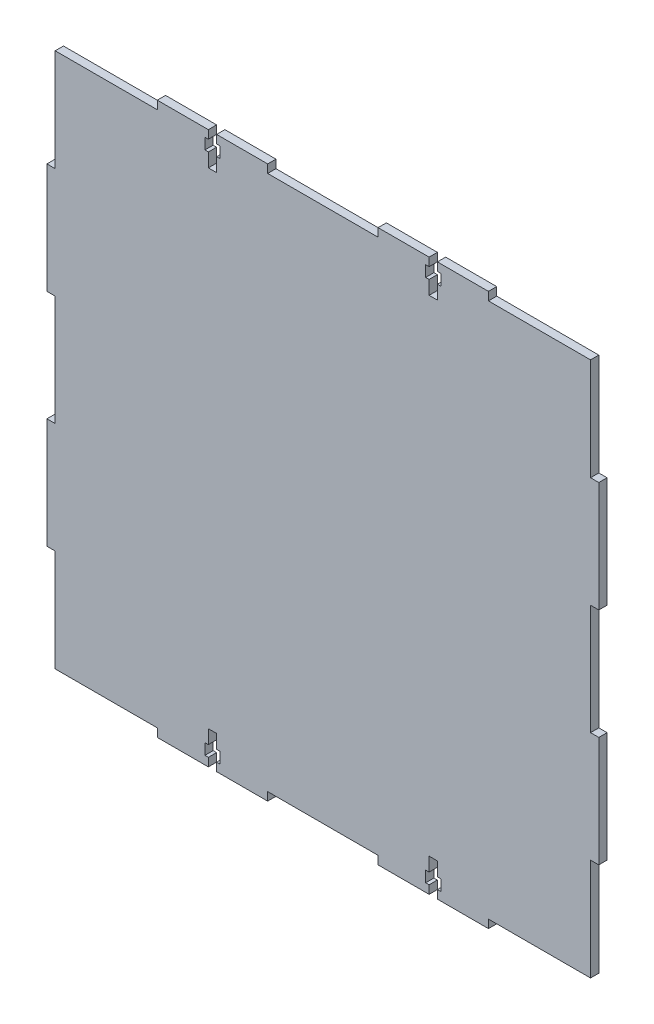
SolidWorks part; units mm, degrees
ref_plane "前视基准面" through (0, 0, 0) normal (0, 0, 1) x (1, 0, 0)
ref_plane "上视基准面" through (0, 0, 0) normal (0, 1, 0) x (1, 0, 0)
ref_plane "右视基准面" through (0, 0, 0) normal (1, 0, 0) x (0, 0, -1)
sketch "草图1" plane through (0, 0, 0) normal (0, 0, 1) x (1, 0, 0)
  line L0 (100, 0) -> (100, -200)
  line L1 (0, 0) -> (200, 0)
  line L2 (0, 0) -> (0, -200)
  line L3 (0, -200) -> (200, -200)
  line L4 (200, 0) -> (200, -200)
  line L5 (0, 0) -> (40, 0)
  line L6 (0, 0) -> (0, -3)
  line L7 (0, -3) -> (40, -3)
  line L8 (40, 0) -> (40, -3)
  line L9 (0, -100) -> (200, -100)
  line L10 (80, 0) -> (80, -3)
  line L11 (80, 0) -> (120, 0)
  line L12 (120, 0) -> (120, -3)
  line L13 (80, -3) -> (120, -3)
  line L14 (160, 0) -> (160, -3)
  line L15 (160, 0) -> (200, 0)
  line L16 (200, 0) -> (200, -3)
  line L17 (160, -3) -> (200, -3)
  line L18 (0, 0) -> (80, 0) construction
  line L19 (200, 0) -> (197, 0)
  line L20 (200, 0) -> (200, -40)
  line L21 (200, -40) -> (197, -40)
  line L22 (197, 0) -> (197, -40)
  line L23 (200, -80) -> (197, -80)
  line L24 (197, -80) -> (197, -120)
  line L25 (200, -120) -> (197, -120)
  line L26 (200, -80) -> (200, -120)
  line L27 (200, -160) -> (197, -160)
  line L28 (197, -160) -> (197, -200)
  line L29 (200, -200) -> (197, -200)
  line L30 (200, -160) -> (200, -200)
  line L31 (200, -200) -> (200, -197)
  line L32 (200, -200) -> (160, -200)
  line L33 (160, -200) -> (160, -197)
  line L34 (200, -197) -> (160, -197)
  line L35 (120, -200) -> (120, -197)
  line L36 (120, -197) -> (80, -197)
  line L37 (80, -200) -> (80, -197)
  line L38 (120, -200) -> (80, -200)
  line L39 (40, -200) -> (40, -197)
  line L40 (40, -197) -> (0, -197)
  line L41 (0, -200) -> (0, -197)
  line L42 (40, -200) -> (0, -200)
  line L43 (0, -200) -> (3, -200)
  line L44 (0, -200) -> (0, -160)
  line L45 (0, -160) -> (3, -160)
  line L46 (3, -200) -> (3, -160)
  line L47 (0, -120) -> (3, -120)
  line L48 (3, -120) -> (3, -80)
  line L49 (0, -80) -> (3, -80)
  line L50 (0, -120) -> (0, -80)
  line L51 (0, -40) -> (3, -40)
  line L52 (3, -40) -> (3, 0)
  line L53 (0, 0) -> (3, 0)
  line L54 (0, -40) -> (0, 0)
  line L55 (142.75, -197) -> (137.25, -197)
  line L56 (58.5, -200) -> (61.5, -200)
  line L57 (58.5, -200) -> (58.5, -188)
  line L58 (58.5, -188) -> (61.5, -188)
  line L59 (61.5, -200) -> (61.5, -188)
  line L60 (57.25, -193) -> (62.75, -193)
  line L61 (57.25, -193) -> (57.25, -197)
  line L62 (57.25, -197) -> (62.75, -197)
  line L63 (62.75, -193) -> (62.75, -197)
  line L64 (137.25, -193) -> (137.25, -197)
  line L65 (142.75, -193) -> (137.25, -193)
  line L66 (142.75, -193) -> (142.75, -197)
  line L67 (141.5, -188) -> (138.5, -188)
  line L68 (138.5, -200) -> (138.5, -188)
  line L69 (141.5, -200) -> (138.5, -200)
  line L70 (141.5, -200) -> (141.5, -188)
  line L71 (141.5, 0) -> (141.5, -12)
  line L72 (141.5, 0) -> (138.5, 0)
  line L73 (138.5, 0) -> (138.5, -12)
  line L74 (141.5, -12) -> (138.5, -12)
  line L75 (142.75, -7) -> (142.75, -3)
  line L76 (142.75, -7) -> (137.25, -7)
  line L77 (137.25, -7) -> (137.25, -3)
  line L78 (142.75, -3) -> (137.25, -3)
  line L79 (57.25, -3) -> (62.75, -3)
  line L80 (62.75, -7) -> (62.75, -3)
  line L81 (57.25, -7) -> (62.75, -7)
  line L82 (57.25, -7) -> (57.25, -3)
  line L83 (58.5, -12) -> (61.5, -12)
  line L84 (61.5, 0) -> (61.5, -12)
  line L85 (58.5, 0) -> (61.5, 0)
  line L86 (58.5, 0) -> (58.5, -12)
  circle A0 centre (100, -100) radius 17.7588
  circle A1 centre (100, -100) radius 17.7588
  circle A2 centre (100, -100) radius 17.7588
  circle A3 centre (100, -100) radius 17.7588
  dimension "D1" = 200
  dimension "D2" = 200
  dimension "D3" = 40
  dimension "D4" = 3
  dimension "D6" = 80
  dimension "D8" = 3
  dimension "D9" = 12
  dimension "D10" = 18.5
  dimension "D11" = 5.5
  dimension "D12" = 1.25
  dimension "D13" = 4
  dimension "D14" = 3
  dimension "D5" = 3
  dimension "D7" = 4
extrude "凸台-拉伸1" add sketch "草图1" along normal blind 3 contours A0 L0 L13 L10 L1 L8 L7 L52 L51 L2 L49 L48 L9 | A0 L9 L48 L47 L2 L45 L46 L40 L39 L3 L37 L36 L0 | A0 L0 L36 L35 L3 L33 L34 L28 L27 L4 L25 L24 L9 | A0 L9 L24 L23 L4 L21 L22 L17 L14 L1 L12 L13 L0 | L9 A0 L0 | L0 A0 L9 | L9 A0 L0 | L0 A0 L9
